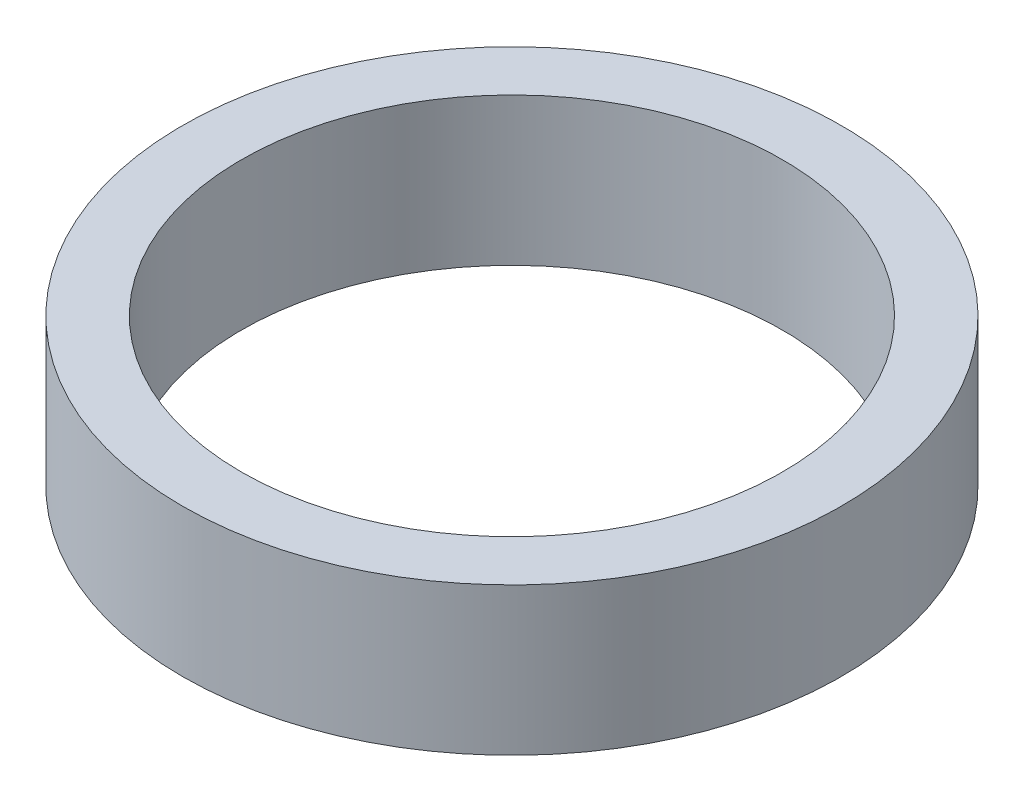
SolidWorks part; units mm, degrees
material "ABS"
ref_plane "Front Plane" through (0, 0, 0) normal (0, 0, 1) x (1, 0, 0)
ref_plane "Top Plane" through (0, 0, 0) normal (0, 1, 0) x (1, 0, 0)
ref_plane "Right Plane" through (0, 0, 0) normal (1, 0, 0) x (0, 0, -1)
sketch "Sketch1" plane through (0, 0, 0) normal (0, 1, 0) x (1, 0, 0)
  circle A0 centre (0, 0) radius 2.75
  circle A1 centre (0, 0) radius 3.35
  dimension "D1" = 5.5
  dimension "D2" = 6.7
extrude "Boss-Extrude1" add sketch "Sketch1" along normal blind 1.5
